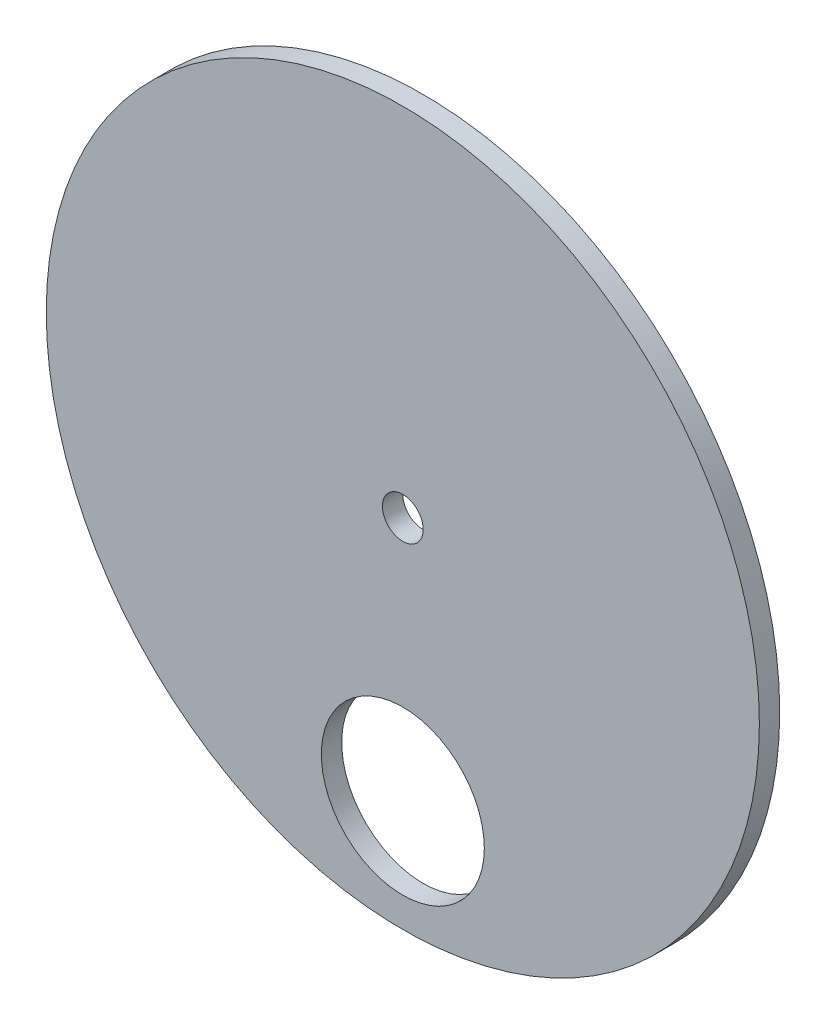
SolidWorks part; units mm, degrees
ref_plane "Front Plane" through (0, 0, 0) normal (0, 0, 1) x (1, 0, 0)
ref_plane "Top Plane" through (0, 0, 0) normal (0, 1, 0) x (1, 0, 0)
ref_plane "Right Plane" through (0, 0, 0) normal (1, 0, 0) x (0, 0, -1)
sketch "Sketch1" plane through (0, 0, 0) normal (0, 0, 1) x (1, 0, 0)
  line L2 (0, 0) -> (0, -175)
  circle A0 centre (0, 0) radius 175
  circle A1 centre (0, -120.3903) radius 40
  circle A2 centre (0, 0) radius 10
extrude "Boss-Extrude3" add sketch "Sketch1" along normal blind 10
